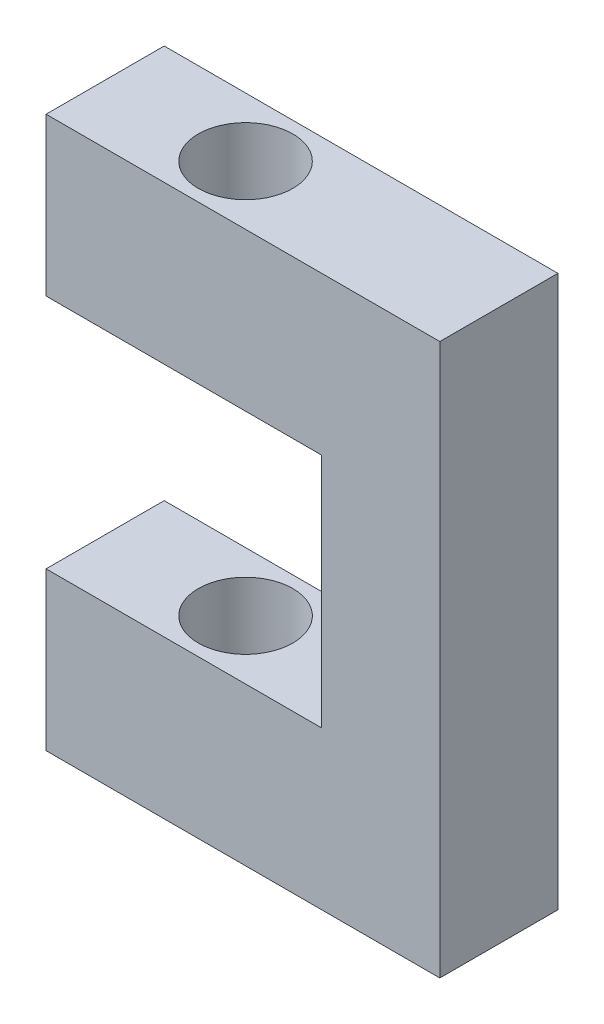
SolidWorks part; units mm, degrees
ref_plane "Front Plane" through (0, 0, 0) normal (0, 0, 1) x (1, 0, 0)
ref_plane "Top Plane" through (0, 0, 0) normal (0, 1, 0) x (1, 0, 0)
ref_plane "Right Plane" through (0, 0, 0) normal (1, 0, 0) x (0, 0, -1)
sketch "Sketch3" plane through (0, 0, 0) normal (0, 0, 1) x (1, 0, 0)
  line L0 (0, 0) -> (50, 0)
  line L1 (50, 0) -> (50, -70)
  line L2 (50, -70) -> (0, -70)
  line L3 (0, 0) -> (0, -20)
  line L4 (0, -20) -> (35, -20)
  line L5 (35, -20) -> (35, -50)
  line L6 (35, -50) -> (0, -50)
  line L7 (0, -50) -> (0, -70)
  dimension "D1" = 50
  dimension "D2" = 50
  dimension "D3" = 70
  dimension "D4" = 20
  dimension "D5" = 20
  dimension "D6" = 35
extrude "Boss-Extrude1" add sketch "Sketch3" along normal blind 15
sketch "Sketch5" plane through (0, 0, 0) normal (0, 1, 0) x (1, 0, 0)
  line L0 (17.8319, -15) -> (17.8319, 0) construction
  line L1 (50, -15) -> (0, -15) construction
  line L2 (50, 0) -> (0, 0) construction
  circle A1 centre (17.8319, -7.5) radius 6
  dimension "D1" = 12
extrude "Cut-Extrude1" cut sketch "Sketch5" against normal blind 81
fillet "Fillet1" [suppressed] radius 5
